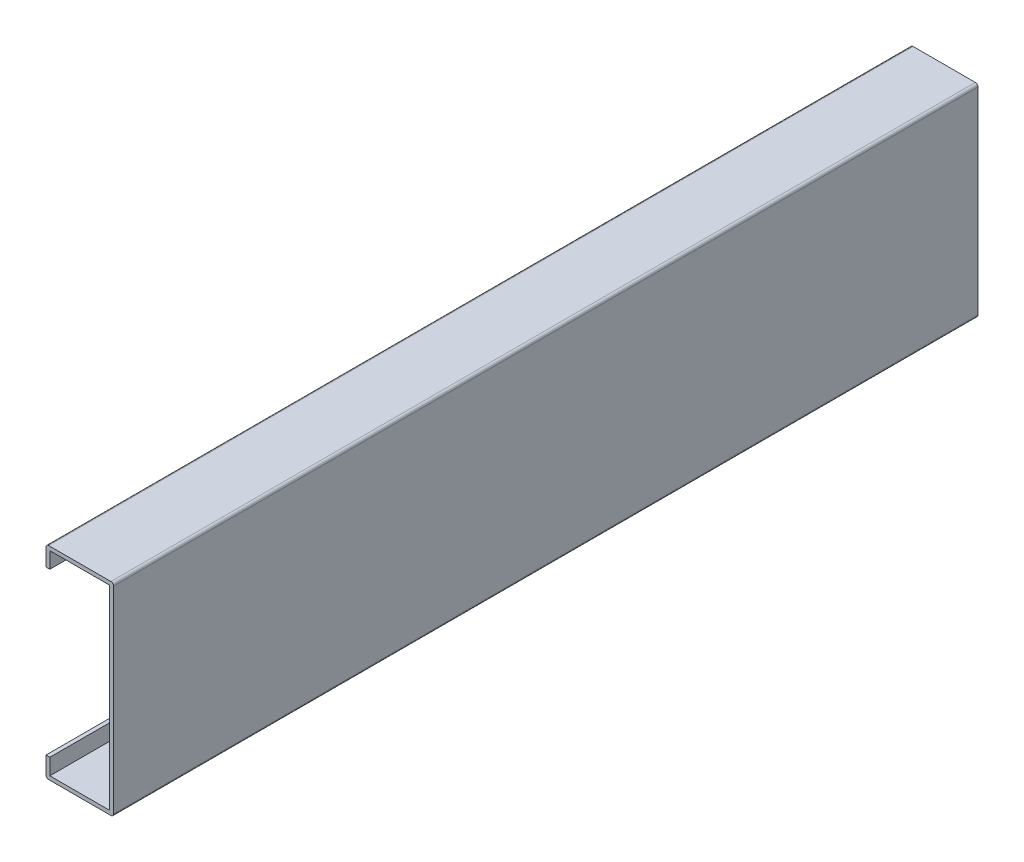
SolidWorks part; units mm, degrees
ref_plane "Alzado" through (0, 0, 0) normal (0, 0, 1) x (1, 0, 0)
ref_plane "Planta" through (0, 0, 0) normal (0, 1, 0) x (1, 0, 0)
ref_plane "Vista lateral" through (0, 0, 0) normal (1, 0, 0) x (0, 0, -1)
sketch "Croquis1" plane through (0, 0, 0) normal (0, 0, 1) x (1, 0, 0)
  line L0 (0, 0) -> (50.8, 0)
  line L1 (50.8, 0) -> (50.8, -152.4)
  line L2 (50.8, -152.4) -> (0, -152.4)
  line L3 (0, -152.4) -> (0, -137.4)
  line L4 (0, 0) -> (0, -15)
  line L5 (2.9, -2.9) -> (2.9, -15)
  line L6 (2.9, -2.9) -> (47.9, -2.9)
  line L7 (47.9, -2.9) -> (47.9, -149.5)
  line L8 (47.9, -149.5) -> (2.9, -149.5)
  line L9 (2.9, -149.5) -> (2.9, -137.4)
  line L10 (2.9, -15) -> (0, -15)
  line L11 (2.9, -137.4) -> (0, -137.4)
  dimension "D1" = 152.4
  dimension "D2" = 50.8
  dimension "D3" = 15
  dimension "D4" = 15
  dimension "D5" = 2.9
extrude "Saliente-Extruir1" add sketch "Croquis1" along normal blind 650
fillet "Redondeo1" radius 2 4 edges at (50.8, 0, 325) (0, 0, 325) (0, -152.4, 325) (50.8, -152.4, 325)
